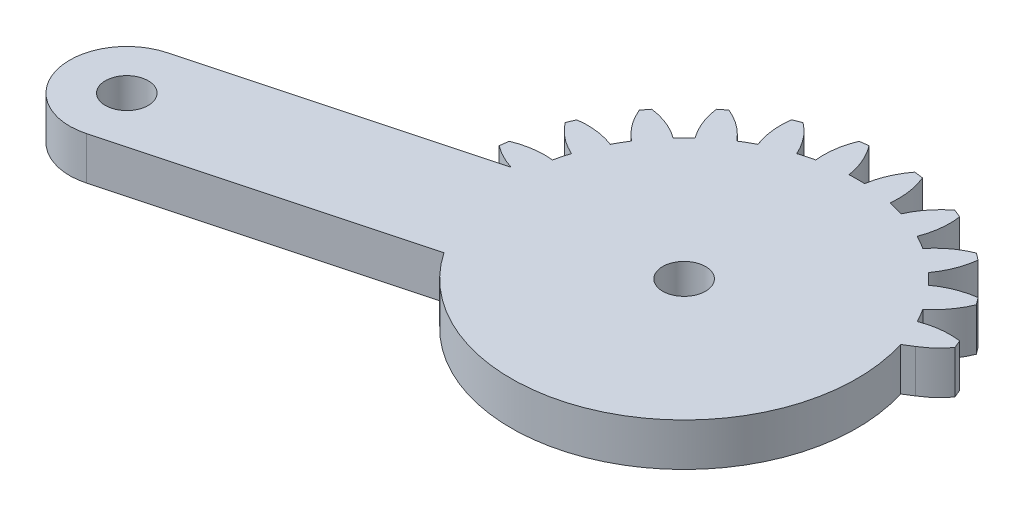
SolidWorks part; units mm, degrees
ref_plane "Front Plane" through (0, 0, 0) normal (0, 0, 1) x (1, 0, 0)
ref_plane "Top Plane" through (0, 0, 0) normal (0, 1, 0) x (1, 0, 0)
ref_plane "Right Plane" through (0, 0, 0) normal (1, 0, 0) x (0, 0, -1)
sketch "Sketch1" plane through (0, 0, 0) normal (0, 1, 0) x (1, 0, 0)
  line L0 (20.6437, 4) -> (2.0816, 4)
  line L1 (2.0816, -4) -> (20.6437, -4)
  arc A0 (2.0816, 4) -> (3.5217, 5.3071) centre (-0.7683, 8.5867) ccw
  arc A1 (3.5217, 5.3071) -> (3.2829, 5.8838) centre (-10.1063, 0) ccw
  arc A2 (3.2829, 5.8838) -> (0.6271, 5.5703) centre (2.5684, 0.5313) ccw
  arc A3 (0.6271, 5.5703) -> (0.0844, 6.5103) centre (-10.1063, 0) ccw
  arc A4 (0.0844, 6.5103) -> (1.6838, 8.6535) centre (-3.3089, 10.711) ccw
  arc A5 (1.6838, 8.6535) -> (1.3038, 9.1487) centre (-10.1063, 0) ccw
  arc A6 (1.3038, 9.1487) -> (-1.1803, 8.1585) centre (1.999, 3.7936) ccw
  arc A7 (-1.1803, 8.1585) -> (-1.9479, 8.926) centre (-10.1063, 0) ccw
  arc A8 (-1.9479, 8.926) -> (-0.9576, 11.4102) centre (-6.3127, 12.1053) ccw
  arc A9 (-0.9576, 11.4102) -> (-1.4528, 11.7901) centre (-10.1063, 0) ccw
  arc A10 (-1.4528, 11.7901) -> (-3.596, 10.1907) centre (0.6046, 6.7975) ccw
  arc A11 (-3.596, 10.1907) -> (-4.5361, 10.7334) centre (-10.1063, 0) ccw
  arc A12 (-4.5361, 10.7334) -> (-4.2225, 13.3892) centre (-9.5751, 12.6747) ccw
  arc A13 (-4.2225, 13.3892) -> (-4.7992, 13.6281) centre (-10.1063, 0) ccw
  arc A14 (-4.7992, 13.6281) -> (-6.4554, 11.5285) centre (-1.5196, 9.3381) ccw
  arc A15 (-6.4554, 11.5285) -> (-7.5039, 11.8094) centre (-10.1063, 0) ccw
  arc A16 (-7.5039, 11.8094) -> (-7.8884, 14.4558) centre (-12.8736, 12.3803) ccw
  arc A17 (-7.8884, 14.4558) -> (-8.5072, 14.5373) centre (-10.1063, 0) ccw
  arc A18 (-8.5072, 14.5373) -> (-9.5636, 12.0806) centre (-4.2291, 11.2423) ccw
  arc A19 (-9.5636, 12.0806) -> (-10.6491, 12.0806) centre (-10.1063, 0) ccw
  arc A20 (-10.6491, 12.0806) -> (-11.7054, 14.5373) centre (-15.9836, 11.2423) ccw
  arc A21 (-11.7054, 14.5373) -> (-12.3243, 14.4558) centre (-10.1063, 0) ccw
  arc A22 (-12.3243, 14.4558) -> (-12.7088, 11.8094) centre (-7.3391, 12.3803) ccw
  arc A23 (-12.7088, 11.8094) -> (-13.7573, 11.5285) centre (-10.1063, 0) ccw
  arc A24 (-13.7573, 11.5285) -> (-15.4135, 13.6281) centre (-18.6931, 9.3381) ccw
  arc A25 (-15.4135, 13.6281) -> (-15.9901, 13.3892) centre (-10.1063, 0) ccw
  arc A26 (-15.9901, 13.3892) -> (-15.6766, 10.7334) centre (-10.6376, 12.6747) ccw
  arc A27 (-15.6766, 10.7334) -> (-16.6166, 10.1907) centre (-10.1063, 0) ccw
  arc A28 (-16.6166, 10.1907) -> (-18.7599, 11.7901) centre (-20.8173, 6.7975) ccw
  arc A29 (-18.7599, 11.7901) -> (-19.255, 11.4102) centre (-10.1063, 0) ccw
  arc A30 (-19.255, 11.4102) -> (-18.2648, 8.926) centre (-13.9, 12.1053) ccw
  arc A31 (-18.2648, 8.926) -> (-19.0324, 8.1585) centre (-10.1063, 0) ccw
  arc A32 (-19.0324, 8.1585) -> (-21.5165, 9.1487) centre (-22.2117, 3.7936) ccw
  arc A33 (-21.5165, 9.1487) -> (-21.8965, 8.6535) centre (-10.1063, 0) ccw
  arc A34 (-21.8965, 8.6535) -> (-20.2971, 6.5103) centre (-16.9038, 10.711) ccw
  arc A35 (-20.2971, 6.5103) -> (-20.8398, 5.5703) centre (-10.1063, 0) ccw
  arc A36 (-20.8398, 5.5703) -> (-23.4956, 5.8838) centre (-22.7811, 0.5313) ccw
  arc A37 (-23.4956, 5.8838) -> (-23.7344, 5.3071) centre (-10.1063, 0) ccw
  arc A38 (-23.7344, 5.3071) -> (-21.6348, 3.6509) centre (-19.4444, 8.5867) ccw
  arc A39 (-21.6348, 3.6509) -> (-21.9157, 2.6025) centre (-10.1063, 0) ccw
  arc A40 (-21.9157, 2.6025) -> (-24.5622, 2.2179) centre (-22.4867, -2.7673) ccw
  arc A41 (-24.5622, 2.2179) -> (-24.6437, 1.5991) centre (-10.1063, 0) ccw
  arc A42 (-24.6437, 1.5991) -> (-22.1869, 0.5427) centre (-21.3486, 5.8773) ccw
  arc A43 (-22.1869, 0.5427) -> (-22.1869, -0.5427) centre (-10.1063, 0) ccw
  arc A44 (-22.1869, -0.5427) -> (-24.6437, -1.5991) centre (-21.3486, -5.8773) ccw
  arc A45 (-24.6437, -1.5991) -> (-24.5622, -2.2179) centre (-10.1063, 0) ccw
  arc A46 (-24.5622, -2.2179) -> (-21.9157, -2.6025) centre (-22.4867, 2.7673) ccw
  arc A47 (-21.9157, -2.6025) -> (-21.6348, -3.6509) centre (-10.1063, 0) ccw
  arc A48 (-21.6348, -3.6509) -> (-23.7344, -5.3071) centre (-19.4444, -8.5867) ccw
  arc A49 (-23.7344, -5.3071) -> (-23.4956, -5.8838) centre (-10.1063, 0) ccw
  arc A50 (-23.4956, -5.8838) -> (-20.8398, -5.5703) centre (-22.7811, -0.5313) ccw
  arc A51 (-20.8398, -5.5703) -> (-20.2971, -6.5103) centre (-10.1063, 0) ccw
  arc A52 (-20.2971, -6.5103) -> (-21.8965, -8.6535) centre (-16.9038, -10.711) ccw
  arc A53 (-21.8965, -8.6535) -> (-21.5165, -9.1487) centre (-10.1063, 0) ccw
  arc A54 (-21.5165, -9.1487) -> (-19.0324, -8.1585) centre (-22.2117, -3.7936) ccw
  arc A55 (-19.0324, -8.1585) -> (-18.2648, -8.926) centre (-10.1063, 0) ccw
  arc A56 (-18.2648, -8.926) -> (-19.255, -11.4102) centre (-13.9, -12.1053) ccw
  arc A57 (-19.255, -11.4102) -> (-18.7599, -11.7901) centre (-10.1063, 0) ccw
  arc A58 (-18.7599, -11.7901) -> (-16.6166, -10.1907) centre (-20.8173, -6.7975) ccw
  arc A59 (-16.6166, -10.1907) -> (-15.6766, -10.7334) centre (-10.1063, 0) ccw
  arc A60 (-15.6766, -10.7334) -> (-15.9901, -13.3892) centre (-10.6376, -12.6747) ccw
  arc A61 (-15.9901, -13.3892) -> (-15.4135, -13.6281) centre (-10.1063, 0) ccw
  arc A62 (-15.4135, -13.6281) -> (-13.7573, -11.5285) centre (-18.6931, -9.3381) ccw
  arc A63 (-13.7573, -11.5285) -> (-12.7088, -11.8094) centre (-10.1063, 0) ccw
  arc A64 (-12.7088, -11.8094) -> (-12.3243, -14.4558) centre (-7.3391, -12.3803) ccw
  arc A65 (-12.3243, -14.4558) -> (-11.7054, -14.5373) centre (-10.1063, 0) ccw
  arc A66 (-11.7054, -14.5373) -> (-10.6491, -12.0806) centre (-15.9836, -11.2423) ccw
  arc A67 (-10.6491, -12.0806) -> (-9.5636, -12.0806) centre (-10.1063, 0) ccw
  arc A68 (-9.5636, -12.0806) -> (-8.5072, -14.5373) centre (-4.2291, -11.2423) ccw
  arc A69 (-8.5072, -14.5373) -> (-7.8884, -14.4558) centre (-10.1063, 0) ccw
  arc A70 (-7.8884, -14.4558) -> (-7.5039, -11.8094) centre (-12.8736, -12.3803) ccw
  arc A71 (-7.5039, -11.8094) -> (-6.4554, -11.5285) centre (-10.1063, 0) ccw
  arc A72 (-6.4554, -11.5285) -> (-4.7992, -13.6281) centre (-1.5196, -9.3381) ccw
  arc A73 (-4.7992, -13.6281) -> (-4.2225, -13.3892) centre (-10.1063, 0) ccw
  arc A74 (-4.2225, -13.3892) -> (-4.5361, -10.7334) centre (-9.5751, -12.6747) ccw
  arc A75 (-4.5361, -10.7334) -> (-3.596, -10.1907) centre (-10.1063, 0) ccw
  arc A76 (-3.596, -10.1907) -> (-1.4528, -11.7901) centre (0.6046, -6.7975) ccw
  arc A77 (-1.4528, -11.7901) -> (-0.9576, -11.4102) centre (-10.1063, 0) ccw
  arc A78 (-0.9576, -11.4102) -> (-1.9479, -8.926) centre (-6.3127, -12.1053) ccw
  arc A79 (-1.9479, -8.926) -> (-1.1803, -8.1585) centre (-10.1063, 0) ccw
  arc A80 (-1.1803, -8.1585) -> (1.3038, -9.1487) centre (1.999, -3.7936) ccw
  arc A81 (1.3038, -9.1487) -> (1.6838, -8.6535) centre (-10.1063, 0) ccw
  arc A82 (1.6838, -8.6535) -> (0.0844, -6.5103) centre (-3.3089, -10.711) ccw
  arc A83 (0.0844, -6.5103) -> (0.6271, -5.5703) centre (-10.1063, 0) ccw
  arc A84 (0.6271, -5.5703) -> (3.2829, -5.8838) centre (2.5684, -0.5313) ccw
  arc A85 (3.2829, -5.8838) -> (3.5217, -5.3071) centre (-10.1063, 0) ccw
  arc A86 (3.5217, -5.3071) -> (2.0816, -4) centre (-0.7683, -8.5867) ccw
  arc A87 (20.6437, -4) -> (20.6437, 4) centre (20.6437, 0) ccw
  circle A88 centre (-10.1063, 0) radius 1.5
  circle A89 centre (20.6437, 0) radius 1.5
  dimension "D1" = 3
  dimension "D2" = 3
extrude "Boss-Extrude1" add sketch "Sketch1" along normal blind 3
sketch "Sketch3" plane through (0, 3, 0) normal (0, 1, 0) x (1, 0, 0)
  line L0 (-10.1063, 0) -> (-40.8563, 0) construction
  line L1 (-10.1063, 0) -> (-40.8563, -8.2394)
  line L2 (-11.1416, 3.8637) -> (-41.8916, -4.3757)
  line L3 (-9.0711, -3.8637) -> (-39.8211, -12.1031)
  circle A0 centre (-10.1063, 0) radius 1.5
  circle A1 centre (20.6437, 0) radius 1.5 construction
  circle A2 centre (20.6437, 0) radius 1.5
  circle A3 centre (-40.8563, -8.2394) radius 1.5
  circle A4 centre (-40.8563, -8.2394) radius 4
  circle A5 centre (-10.1063, 0) radius 4
  dimension "D2" = 3
  dimension "D5" = 3
  dimension "D6" = 8
  dimension "D7" = 8
  dimension "D1" = 30.75
  dimension "D3" = 30.75
  dimension "D4" = 15
extrude "Boss-Extrude2" add sketch "Sketch3" against normal blind 3
sketch "Sketch4" plane through (0, 3, 0) normal (0, 1, 0) x (1, 0, 0)
  line L0 (20.6437, 4) -> (2.0816, 4) construction
  line L1 (2.0816, -4) -> (20.6437, -4) construction
  line L2 (20.6437, 4) -> (2.0816, 4)
  line L3 (2.0816, -4) -> (20.6437, -4)
  line L4 (2.0816, 4) -> (1.4381, 3.6001)
  line L5 (-20.8438, -7.0182) -> (-20.0942, -6.8174)
  line L8 (-22.9143, 0.7092) -> (-41.8916, -4.3757)
  line L9 (-39.8211, -12.1031) -> (-20.8438, -7.0182)
  line L10 (2.0816, -4) -> (20.6437, -4)
  line L11 (20.6437, 4) -> (2.0816, 4)
  line L12 (-22.9143, 0.7092) -> (-41.8916, -4.3757)
  line L13 (-39.8211, -12.1031) -> (-20.8438, -7.0182)
  line L14 (2.0816, -4) -> (20.6437, -4)
  line L15 (20.6437, 4) -> (2.0816, 4)
  circle A0 centre (-10.1063, 0) radius 12.0927
  arc A1 (3.2829, 5.8838) -> (0.6271, 5.5703) centre (2.5684, 0.5313) ccw construction
  arc A2 (3.5217, 5.3071) -> (3.2829, 5.8838) centre (-10.1063, 0) ccw construction
  arc A3 (2.0816, 4) -> (3.5217, 5.3071) centre (-0.7683, 8.5867) ccw construction
  arc A4 (20.6437, -4) -> (20.6437, 4) centre (20.6437, 0) ccw construction
  arc A5 (3.5217, -5.3071) -> (2.0816, -4) centre (-0.7683, -8.5867) ccw construction
  arc A6 (3.2829, -5.8838) -> (3.5217, -5.3071) centre (-10.1063, 0) ccw construction
  arc A7 (0.6271, -5.5703) -> (3.2829, -5.8838) centre (2.5684, -0.5313) ccw construction
  arc A8 (3.2829, 5.8838) -> (0.6271, 5.5703) centre (2.5684, 0.5313) ccw
  arc A9 (3.5217, 5.3071) -> (3.2829, 5.8838) centre (-10.1063, 0) ccw
  arc A10 (2.0816, 4) -> (3.5217, 5.3071) centre (-0.7683, 8.5867) ccw
  arc A11 (20.6437, -4) -> (20.6437, 4) centre (20.6437, 0) ccw
  arc A12 (3.5217, -5.3071) -> (2.0816, -4) centre (-0.7683, -8.5867) ccw
  arc A13 (3.2829, -5.8838) -> (3.5217, -5.3071) centre (-10.1063, 0) ccw
  arc A14 (0.6271, -5.5703) -> (3.2829, -5.8838) centre (2.5684, -0.5313) ccw
  arc A95 (-24.6437, 1.5991) -> (-22.9143, 0.7092) centre (-21.3486, 5.8773) ccw
  arc A96 (-41.8916, -4.3757) -> (-39.8211, -12.1031) centre (-40.8563, -8.2394) ccw
  arc A97 (-20.8438, -7.0182) -> (-21.8965, -8.6535) centre (-16.9038, -10.711) ccw
  arc A98 (-21.8965, -8.6535) -> (-21.5165, -9.1487) centre (-10.1063, 0) ccw
  arc A99 (-21.5165, -9.1487) -> (-19.0324, -8.1585) centre (-22.2117, -3.7936) ccw
  arc A100 (-19.0324, -8.1585) -> (-18.2648, -8.926) centre (-10.1063, 0) ccw
  arc A101 (-18.2648, -8.926) -> (-19.255, -11.4102) centre (-13.9, -12.1053) ccw
  arc A102 (-19.255, -11.4102) -> (-18.7599, -11.7901) centre (-10.1063, 0) ccw
  arc A103 (-18.7599, -11.7901) -> (-16.6166, -10.1907) centre (-20.8173, -6.7975) ccw
  arc A104 (-16.6166, -10.1907) -> (-15.6766, -10.7334) centre (-10.1063, 0) ccw
  arc A105 (-15.6766, -10.7334) -> (-15.9901, -13.3892) centre (-10.6376, -12.6747) ccw
  arc A106 (-15.9901, -13.3892) -> (-15.4135, -13.6281) centre (-10.1063, 0) ccw
  arc A107 (-15.4135, -13.6281) -> (-13.7573, -11.5285) centre (-18.6931, -9.3381) ccw
  arc A108 (-13.7573, -11.5285) -> (-12.7088, -11.8094) centre (-10.1063, 0) ccw
  arc A109 (-12.7088, -11.8094) -> (-12.3243, -14.4558) centre (-7.3391, -12.3803) ccw
  arc A110 (-12.3243, -14.4558) -> (-11.7054, -14.5373) centre (-10.1063, 0) ccw
  arc A111 (-11.7054, -14.5373) -> (-10.6491, -12.0806) centre (-15.9836, -11.2423) ccw
  arc A112 (-10.6491, -12.0806) -> (-9.5636, -12.0806) centre (-10.1063, 0) ccw
  arc A113 (-9.5636, -12.0806) -> (-8.5072, -14.5373) centre (-4.2291, -11.2423) ccw
  arc A114 (-8.5072, -14.5373) -> (-7.8884, -14.4558) centre (-10.1063, 0) ccw
  arc A115 (-7.8884, -14.4558) -> (-7.5039, -11.8094) centre (-12.8736, -12.3803) ccw
  arc A116 (-7.5039, -11.8094) -> (-6.4554, -11.5285) centre (-10.1063, 0) ccw
  arc A117 (-6.4554, -11.5285) -> (-4.7992, -13.6281) centre (-1.5196, -9.3381) ccw
  arc A118 (-4.7992, -13.6281) -> (-4.2225, -13.3892) centre (-10.1063, 0) ccw
  arc A119 (-4.2225, -13.3892) -> (-4.5361, -10.7334) centre (-9.5751, -12.6747) ccw
  arc A120 (-4.5361, -10.7334) -> (-3.596, -10.1907) centre (-10.1063, 0) ccw
  arc A121 (-3.596, -10.1907) -> (-1.4528, -11.7901) centre (0.6046, -6.7975) ccw
  arc A122 (-1.4528, -11.7901) -> (-0.9576, -11.4102) centre (-10.1063, 0) ccw
  arc A123 (-0.9576, -11.4102) -> (-1.9479, -8.926) centre (-6.3127, -12.1053) ccw
  arc A124 (-1.9479, -8.926) -> (-1.1803, -8.1585) centre (-10.1063, 0) ccw
  arc A125 (-1.1803, -8.1585) -> (1.3038, -9.1487) centre (1.999, -3.7936) ccw
  arc A126 (1.3038, -9.1487) -> (1.6838, -8.6535) centre (-10.1063, 0) ccw
  arc A127 (1.6838, -8.6535) -> (0.0844, -6.5103) centre (-3.3089, -10.711) ccw
  arc A128 (0.0844, -6.5103) -> (0.6271, -5.5703) centre (-10.1063, 0) ccw
  arc A129 (0.6271, -5.5703) -> (3.2829, -5.8838) centre (2.5684, -0.5313) ccw
  arc A130 (3.2829, -5.8838) -> (3.5217, -5.3071) centre (-10.1063, 0) ccw
  arc A131 (3.5217, -5.3071) -> (2.0816, -4) centre (-0.7683, -8.5867) ccw
  arc A132 (20.6437, -4) -> (20.6437, 4) centre (20.6437, 0) ccw
  arc A133 (2.0816, 4) -> (3.5217, 5.3071) centre (-0.7683, 8.5867) ccw
  arc A134 (3.5217, 5.3071) -> (3.2829, 5.8838) centre (-10.1063, 0) ccw
  arc A135 (3.2829, 5.8838) -> (0.6271, 5.5703) centre (2.5684, 0.5313) ccw
  arc A136 (0.6271, 5.5703) -> (0.0844, 6.5103) centre (-10.1063, 0) ccw
  arc A137 (0.0844, 6.5103) -> (1.6838, 8.6535) centre (-3.3089, 10.711) ccw
  arc A138 (1.6838, 8.6535) -> (1.3038, 9.1487) centre (-10.1063, 0) ccw
  arc A139 (1.3038, 9.1487) -> (-1.1803, 8.1585) centre (1.999, 3.7936) ccw
  arc A140 (-1.1803, 8.1585) -> (-1.9479, 8.926) centre (-10.1063, 0) ccw
  arc A141 (-1.9479, 8.926) -> (-0.9576, 11.4102) centre (-6.3127, 12.1053) ccw
  arc A142 (-0.9576, 11.4102) -> (-1.4528, 11.7901) centre (-10.1063, 0) ccw
  arc A143 (-1.4528, 11.7901) -> (-3.596, 10.1907) centre (0.6046, 6.7975) ccw
  arc A144 (-3.596, 10.1907) -> (-4.5361, 10.7334) centre (-10.1063, 0) ccw
  arc A145 (-4.5361, 10.7334) -> (-4.2225, 13.3892) centre (-9.5751, 12.6747) ccw
  arc A146 (-4.2225, 13.3892) -> (-4.7992, 13.6281) centre (-10.1063, 0) ccw
  arc A147 (-4.7992, 13.6281) -> (-6.4554, 11.5285) centre (-1.5196, 9.3381) ccw
  arc A148 (-6.4554, 11.5285) -> (-7.5039, 11.8094) centre (-10.1063, 0) ccw
  arc A149 (-7.5039, 11.8094) -> (-7.8884, 14.4558) centre (-12.8736, 12.3803) ccw
  arc A150 (-7.8884, 14.4558) -> (-8.5072, 14.5373) centre (-10.1063, 0) ccw
  arc A151 (-8.5072, 14.5373) -> (-9.5636, 12.0806) centre (-4.2291, 11.2423) ccw
  arc A152 (-9.5636, 12.0806) -> (-10.6491, 12.0806) centre (-10.1063, 0) ccw
  arc A153 (-10.6491, 12.0806) -> (-11.7054, 14.5373) centre (-15.9836, 11.2423) ccw
  arc A154 (-11.7054, 14.5373) -> (-12.3243, 14.4558) centre (-10.1063, 0) ccw
  arc A155 (-12.3243, 14.4558) -> (-12.7088, 11.8094) centre (-7.3391, 12.3803) ccw
  arc A156 (-12.7088, 11.8094) -> (-13.7573, 11.5285) centre (-10.1063, 0) ccw
  arc A157 (-13.7573, 11.5285) -> (-15.4135, 13.6281) centre (-18.6931, 9.3381) ccw
  arc A158 (-15.4135, 13.6281) -> (-15.9901, 13.3892) centre (-10.1063, 0) ccw
  arc A159 (-15.9901, 13.3892) -> (-15.6766, 10.7334) centre (-10.6376, 12.6747) ccw
  arc A160 (-15.6766, 10.7334) -> (-16.6166, 10.1907) centre (-10.1063, 0) ccw
  arc A161 (-16.6166, 10.1907) -> (-18.7599, 11.7901) centre (-20.8173, 6.7975) ccw
  arc A162 (-18.7599, 11.7901) -> (-19.255, 11.4102) centre (-10.1063, 0) ccw
  arc A163 (-19.255, 11.4102) -> (-18.2648, 8.926) centre (-13.9, 12.1053) ccw
  arc A164 (-18.2648, 8.926) -> (-19.0324, 8.1585) centre (-10.1063, 0) ccw
  arc A165 (-19.0324, 8.1585) -> (-21.5165, 9.1487) centre (-22.2117, 3.7936) ccw
  arc A166 (-21.5165, 9.1487) -> (-21.8965, 8.6535) centre (-10.1063, 0) ccw
  arc A167 (-21.8965, 8.6535) -> (-20.2971, 6.5103) centre (-16.9038, 10.711) ccw
  arc A168 (-20.2971, 6.5103) -> (-20.8398, 5.5703) centre (-10.1063, 0) ccw
  arc A169 (-20.8398, 5.5703) -> (-23.4956, 5.8838) centre (-22.7811, 0.5313) ccw
  arc A170 (-23.4956, 5.8838) -> (-23.7344, 5.3071) centre (-10.1063, 0) ccw
  arc A171 (-23.7344, 5.3071) -> (-21.6348, 3.6509) centre (-19.4444, 8.5867) ccw
  arc A172 (-21.6348, 3.6509) -> (-21.9157, 2.6025) centre (-10.1063, 0) ccw
  arc A173 (-21.9157, 2.6025) -> (-24.5622, 2.2179) centre (-22.4867, -2.7673) ccw
  arc A174 (-24.5622, 2.2179) -> (-24.6437, 1.5991) centre (-10.1063, 0) ccw
  arc A175 (-24.6437, 1.5991) -> (-22.9143, 0.7092) centre (-21.3486, 5.8773) ccw
  arc A176 (-41.8916, -4.3757) -> (-39.8211, -12.1031) centre (-40.8563, -8.2394) ccw
  arc A177 (-20.8438, -7.0182) -> (-21.8965, -8.6535) centre (-16.9038, -10.711) ccw
  arc A178 (-21.8965, -8.6535) -> (-21.5165, -9.1487) centre (-10.1063, 0) ccw
  arc A179 (-21.5165, -9.1487) -> (-19.0324, -8.1585) centre (-22.2117, -3.7936) ccw
  arc A180 (-19.0324, -8.1585) -> (-18.2648, -8.926) centre (-10.1063, 0) ccw
  arc A181 (-18.2648, -8.926) -> (-19.255, -11.4102) centre (-13.9, -12.1053) ccw
  arc A182 (-19.255, -11.4102) -> (-18.7599, -11.7901) centre (-10.1063, 0) ccw
  arc A183 (-18.7599, -11.7901) -> (-16.6166, -10.1907) centre (-20.8173, -6.7975) ccw
  arc A184 (-16.6166, -10.1907) -> (-15.6766, -10.7334) centre (-10.1063, 0) ccw
  arc A185 (-15.6766, -10.7334) -> (-15.9901, -13.3892) centre (-10.6376, -12.6747) ccw
  arc A186 (-15.9901, -13.3892) -> (-15.4135, -13.6281) centre (-10.1063, 0) ccw
  arc A187 (-15.4135, -13.6281) -> (-13.7573, -11.5285) centre (-18.6931, -9.3381) ccw
  arc A188 (-13.7573, -11.5285) -> (-12.7088, -11.8094) centre (-10.1063, 0) ccw
  arc A189 (-12.7088, -11.8094) -> (-12.3243, -14.4558) centre (-7.3391, -12.3803) ccw
  arc A190 (-12.3243, -14.4558) -> (-11.7054, -14.5373) centre (-10.1063, 0) ccw
  arc A191 (-11.7054, -14.5373) -> (-10.6491, -12.0806) centre (-15.9836, -11.2423) ccw
  arc A192 (-10.6491, -12.0806) -> (-9.5636, -12.0806) centre (-10.1063, 0) ccw
  arc A193 (-9.5636, -12.0806) -> (-8.5072, -14.5373) centre (-4.2291, -11.2423) ccw
  arc A194 (-8.5072, -14.5373) -> (-7.8884, -14.4558) centre (-10.1063, 0) ccw
  arc A195 (-7.8884, -14.4558) -> (-7.5039, -11.8094) centre (-12.8736, -12.3803) ccw
  arc A196 (-7.5039, -11.8094) -> (-6.4554, -11.5285) centre (-10.1063, 0) ccw
  arc A197 (-6.4554, -11.5285) -> (-4.7992, -13.6281) centre (-1.5196, -9.3381) ccw
  arc A198 (-4.7992, -13.6281) -> (-4.2225, -13.3892) centre (-10.1063, 0) ccw
  arc A199 (-4.2225, -13.3892) -> (-4.5361, -10.7334) centre (-9.5751, -12.6747) ccw
  arc A200 (-4.5361, -10.7334) -> (-3.596, -10.1907) centre (-10.1063, 0) ccw
  arc A201 (-3.596, -10.1907) -> (-1.4528, -11.7901) centre (0.6046, -6.7975) ccw
  arc A202 (-1.4528, -11.7901) -> (-0.9576, -11.4102) centre (-10.1063, 0) ccw
  arc A203 (-0.9576, -11.4102) -> (-1.9479, -8.926) centre (-6.3127, -12.1053) ccw
  arc A204 (-1.9479, -8.926) -> (-1.1803, -8.1585) centre (-10.1063, 0) ccw
  arc A205 (-1.1803, -8.1585) -> (1.3038, -9.1487) centre (1.999, -3.7936) ccw
  arc A206 (1.3038, -9.1487) -> (1.6838, -8.6535) centre (-10.1063, 0) ccw
  arc A207 (1.6838, -8.6535) -> (0.0844, -6.5103) centre (-3.3089, -10.711) ccw
  arc A208 (0.0844, -6.5103) -> (0.6271, -5.5703) centre (-10.1063, 0) ccw
  arc A209 (0.6271, -5.5703) -> (3.2829, -5.8838) centre (2.5684, -0.5313) ccw
  arc A210 (3.2829, -5.8838) -> (3.5217, -5.3071) centre (-10.1063, 0) ccw
  arc A211 (3.5217, -5.3071) -> (2.0816, -4) centre (-0.7683, -8.5867) ccw
  arc A212 (20.6437, -4) -> (20.6437, 4) centre (20.6437, 0) ccw
  arc A213 (2.0816, 4) -> (3.5217, 5.3071) centre (-0.7683, 8.5867) ccw
  arc A214 (3.5217, 5.3071) -> (3.2829, 5.8838) centre (-10.1063, 0) ccw
  arc A215 (3.2829, 5.8838) -> (0.6271, 5.5703) centre (2.5684, 0.5313) ccw
  arc A216 (0.6271, 5.5703) -> (0.0844, 6.5103) centre (-10.1063, 0) ccw
  arc A217 (0.0844, 6.5103) -> (1.6838, 8.6535) centre (-3.3089, 10.711) ccw
  arc A218 (1.6838, 8.6535) -> (1.3038, 9.1487) centre (-10.1063, 0) ccw
  arc A219 (1.3038, 9.1487) -> (-1.1803, 8.1585) centre (1.999, 3.7936) ccw
  arc A220 (-1.1803, 8.1585) -> (-1.9479, 8.926) centre (-10.1063, 0) ccw
  arc A221 (-1.9479, 8.926) -> (-0.9576, 11.4102) centre (-6.3127, 12.1053) ccw
  arc A222 (-0.9576, 11.4102) -> (-1.4528, 11.7901) centre (-10.1063, 0) ccw
  arc A223 (-1.4528, 11.7901) -> (-3.596, 10.1907) centre (0.6046, 6.7975) ccw
  arc A224 (-3.596, 10.1907) -> (-4.5361, 10.7334) centre (-10.1063, 0) ccw
  arc A225 (-4.5361, 10.7334) -> (-4.2225, 13.3892) centre (-9.5751, 12.6747) ccw
  arc A226 (-4.2225, 13.3892) -> (-4.7992, 13.6281) centre (-10.1063, 0) ccw
  arc A227 (-4.7992, 13.6281) -> (-6.4554, 11.5285) centre (-1.5196, 9.3381) ccw
  arc A228 (-6.4554, 11.5285) -> (-7.5039, 11.8094) centre (-10.1063, 0) ccw
  arc A229 (-7.5039, 11.8094) -> (-7.8884, 14.4558) centre (-12.8736, 12.3803) ccw
  arc A230 (-7.8884, 14.4558) -> (-8.5072, 14.5373) centre (-10.1063, 0) ccw
  arc A231 (-8.5072, 14.5373) -> (-9.5636, 12.0806) centre (-4.2291, 11.2423) ccw
  arc A232 (-9.5636, 12.0806) -> (-10.6491, 12.0806) centre (-10.1063, 0) ccw
  arc A233 (-10.6491, 12.0806) -> (-11.7054, 14.5373) centre (-15.9836, 11.2423) ccw
  arc A234 (-11.7054, 14.5373) -> (-12.3243, 14.4558) centre (-10.1063, 0) ccw
  arc A235 (-12.3243, 14.4558) -> (-12.7088, 11.8094) centre (-7.3391, 12.3803) ccw
  arc A236 (-12.7088, 11.8094) -> (-13.7573, 11.5285) centre (-10.1063, 0) ccw
  arc A237 (-13.7573, 11.5285) -> (-15.4135, 13.6281) centre (-18.6931, 9.3381) ccw
  arc A238 (-15.4135, 13.6281) -> (-15.9901, 13.3892) centre (-10.1063, 0) ccw
  arc A239 (-15.9901, 13.3892) -> (-15.6766, 10.7334) centre (-10.6376, 12.6747) ccw
  arc A240 (-15.6766, 10.7334) -> (-16.6166, 10.1907) centre (-10.1063, 0) ccw
  arc A241 (-16.6166, 10.1907) -> (-18.7599, 11.7901) centre (-20.8173, 6.7975) ccw
  arc A242 (-18.7599, 11.7901) -> (-19.255, 11.4102) centre (-10.1063, 0) ccw
  arc A243 (-19.255, 11.4102) -> (-18.2648, 8.926) centre (-13.9, 12.1053) ccw
  arc A244 (-18.2648, 8.926) -> (-19.0324, 8.1585) centre (-10.1063, 0) ccw
  arc A245 (-19.0324, 8.1585) -> (-21.5165, 9.1487) centre (-22.2117, 3.7936) ccw
  arc A246 (-21.5165, 9.1487) -> (-21.8965, 8.6535) centre (-10.1063, 0) ccw
  arc A247 (-21.8965, 8.6535) -> (-20.2971, 6.5103) centre (-16.9038, 10.711) ccw
  arc A248 (-20.2971, 6.5103) -> (-20.8398, 5.5703) centre (-10.1063, 0) ccw
  arc A249 (-20.8398, 5.5703) -> (-23.4956, 5.8838) centre (-22.7811, 0.5313) ccw
  arc A250 (-23.4956, 5.8838) -> (-23.7344, 5.3071) centre (-10.1063, 0) ccw
  arc A251 (-23.7344, 5.3071) -> (-21.6348, 3.6509) centre (-19.4444, 8.5867) ccw
  arc A252 (-21.6348, 3.6509) -> (-21.9157, 2.6025) centre (-10.1063, 0) ccw
  arc A253 (-21.9157, 2.6025) -> (-24.5622, 2.2179) centre (-22.4867, -2.7673) ccw
  arc A254 (-24.5622, 2.2179) -> (-24.6437, 1.5991) centre (-10.1063, 0) ccw
  dimension "D2" = 24.1855
  dimension "D1" = 0
extrude "Cut-Extrude1" cut sketch "Sketch4" against normal blind 3 contours A178 A179 A0 L5 A177 | A182 A183 A0 A181 | A186 A187 A0 A185 | A190 A191 A0 A189 | A194 A195 A0 A193 | A198 A199 A0 A197 | A202 A203 A0 A201 | A206 A207 A0 A205 | A0 A14 A13 A12 L3 A11 L2 L4
